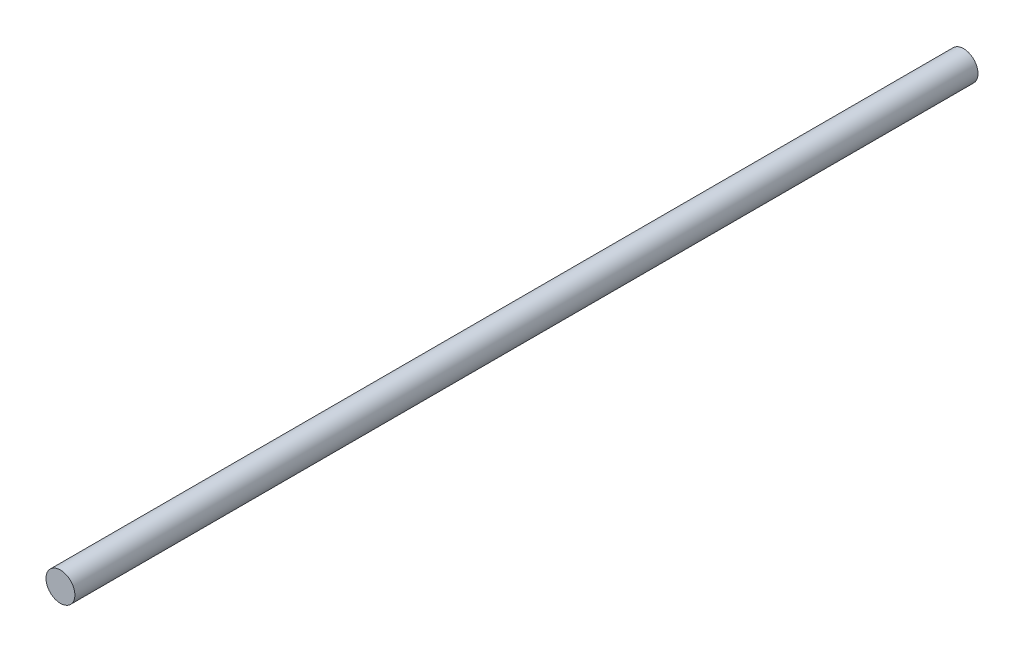
SolidWorks part; units mm, degrees
material "Nickel"
ref_plane "Front Plane" through (0, 0, 0) normal (0, 0, 1) x (1, 0, 0)
ref_plane "Top Plane" through (0, 0, 0) normal (0, 1, 0) x (1, 0, 0)
ref_plane "Right Plane" through (0, 0, 0) normal (1, 0, 0) x (0, 0, -1)
sketch "Sketch1" plane through (0, 0, 0) normal (0, 0, 1) x (1, 0, 0)
  circle A0 centre (-5.9871, 4.9645) radius 4
  dimension "D1" = 8
extrude "Boss-Extrude1" add sketch "Sketch1" along normal blind 250
